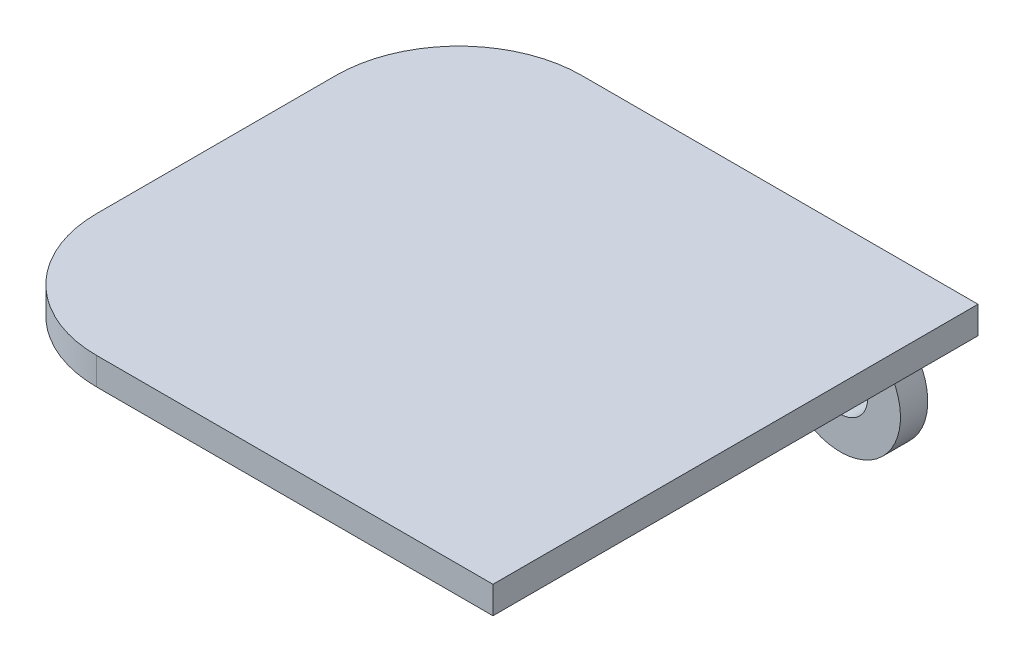
SolidWorks part; units mm, degrees
ref_plane "Front Plane" through (0, 0, 0) normal (0, 0, 1) x (1, 0, 0)
ref_plane "Top Plane" through (0, 0, 0) normal (0, 1, 0) x (1, 0, 0)
ref_plane "Right Plane" through (0, 0, 0) normal (1, 0, 0) x (0, 0, -1)
sketch "Sketch1" plane through (0, 0, 0) normal (0, 1, 0) x (1, 0, 0)
  line L1 (-10, 17.75) -> (19, 17.75)
  line L2 (-19, 8.75) -> (-19, -8.75)
  line L3 (-10, -17.75) -> (19, -17.75)
  line L4 (19, 17.75) -> (19, -17.75)
  line L5 (-19, 17.75) -> (19, -17.75) construction
  line L6 (-19, -17.75) -> (19, 17.75) construction
  arc A0 (-19, -8.75) -> (-10, -17.75) centre (-10, -8.75) ccw
  arc A1 (-10, 17.75) -> (-19, 8.75) centre (-10, 8.75) ccw
  point P0 (0, 0)
  dimension "D3" = 9
  dimension "D1" = 38
  dimension "D2" = 35.5
extrude "Boss-Extrude1" add sketch "Sketch1" along normal blind 2
sketch "Sketch2" plane through (0, 0, -17.75) normal (0, 0, -1) x (-1, 0, 0)
  line L0 (-10.5, 0) -> (-13.6897, -2.5779)
  line L1 (-19, 0) -> (10, 0) construction
  line L2 (-13.6897, -2.5779) -> (-8.1583, -9.4221) construction
  line L3 (-8.1583, -9.4221) -> (3.5, 0)
  line L4 (-10.5, 0) -> (3.5, 0)
  arc A0 (-8.1583, -9.4221) -> (-13.6897, -2.5779) centre (-10.924, -6) cw
  circle A1 centre (-10.924, -6) radius 2
  dimension "D4" = 6
  dimension "D5" = 4
  dimension "D1" = 8.5
  dimension "D2" = 8.8
  dimension "D3" = 14
extrude "Boss-Extrude2" add sketch "Sketch2" against normal blind 2
